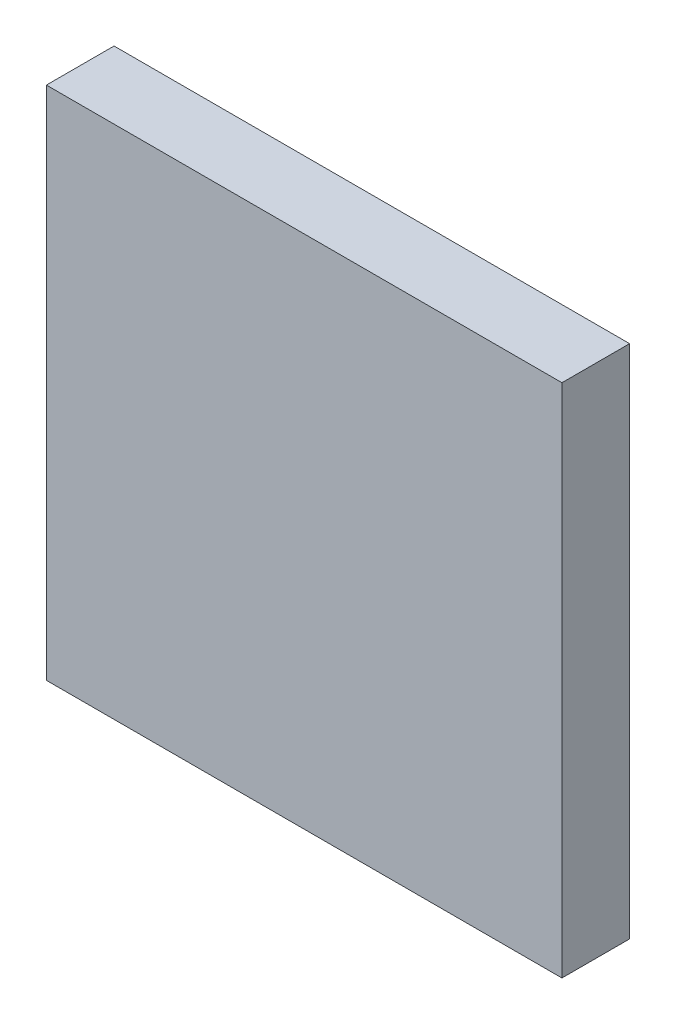
SolidWorks part; units mm, degrees
ref_plane "Front Plane" through (0, 0, 0) normal (0, 0, 1) x (1, 0, 0)
ref_plane "Top Plane" through (0, 0, 0) normal (0, 1, 0) x (1, 0, 0)
ref_plane "Right Plane" through (0, 0, 0) normal (1, 0, 0) x (0, 0, -1)
sketch "Sketch1" plane through (0, 0, 0) normal (0, 0, 1) x (1, 0, 0)
  circle A0 centre (0, 0) radius 7.5
extrude "Boss-Extrude1" add sketch "Sketch1" against normal up to surface (22 mm away)
sketch "Sketch2" plane through (0, 0, 0) normal (0, 0, 1) x (1, 0, 0)
  circle A0 centre (0, 0) radius 10
extrude "Boss-Extrude2" add sketch "Sketch2" along normal offset from surface (3 mm away) 1
sketch "Sketch3" plane through (0, 0, 3) normal (0, 0, 1) x (1, 0, 0)
  line L1 (-38.1, 38.1) -> (38.1, 38.1)
  line L2 (-38.1, 38.1) -> (-38.1, -38.1)
  line L3 (-38.1, -38.1) -> (38.1, -38.1)
  line L4 (38.1, 38.1) -> (38.1, -38.1)
  line L5 (-38.1, 38.1) -> (38.1, -38.1) construction
  line L6 (-38.1, -38.1) -> (38.1, 38.1) construction
  point P0 (0, 0)
extrude "Boss-Extrude3" add sketch "Sketch3" along normal blind 10
